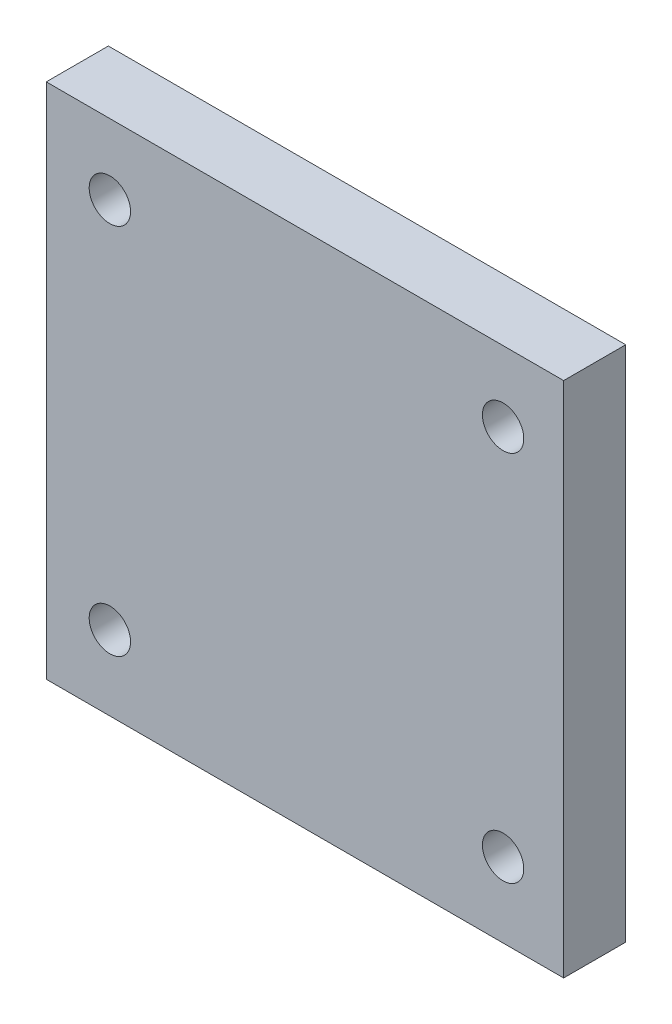
SolidWorks part; units mm, degrees
ref_plane "Plan de face" through (0, 0, 0) normal (0, 0, 1) x (1, 0, 0)
ref_plane "Plan de dessus" through (0, 0, 0) normal (0, 1, 0) x (1, 0, 0)
ref_plane "Plan de droite" through (0, 0, 0) normal (1, 0, 0) x (0, 0, -1)
sketch "Esquisse1" plane through (0, 0, 0) normal (0, 0, 1) x (1, 0, 0)
  line L20 (-13.8151, -12.8134) -> (11.1849, -12.8134)
  line L21 (-13.8151, -12.8134) -> (-13.8151, 12.1866)
  line L22 (-13.8151, 12.1866) -> (11.1849, 12.1866)
  line L23 (11.1849, -12.8134) -> (11.1849, 12.1866)
  circle A0 centre (-10.7416, -9.2096) radius 1
  circle A1 centre (-10.7416, 8.7904) radius 1
  circle A2 centre (8.2584, -9.2096) radius 1
  circle A3 centre (8.2584, 8.7904) radius 1
  dimension "D3" = 2
  dimension "D4" = 2
  dimension "D5" = 2
  dimension "D6" = 2
  dimension "D2" = 25
  dimension "D15" = 25
extrude "Boss.-Extru.1" add sketch "Esquisse1" along normal blind 3
